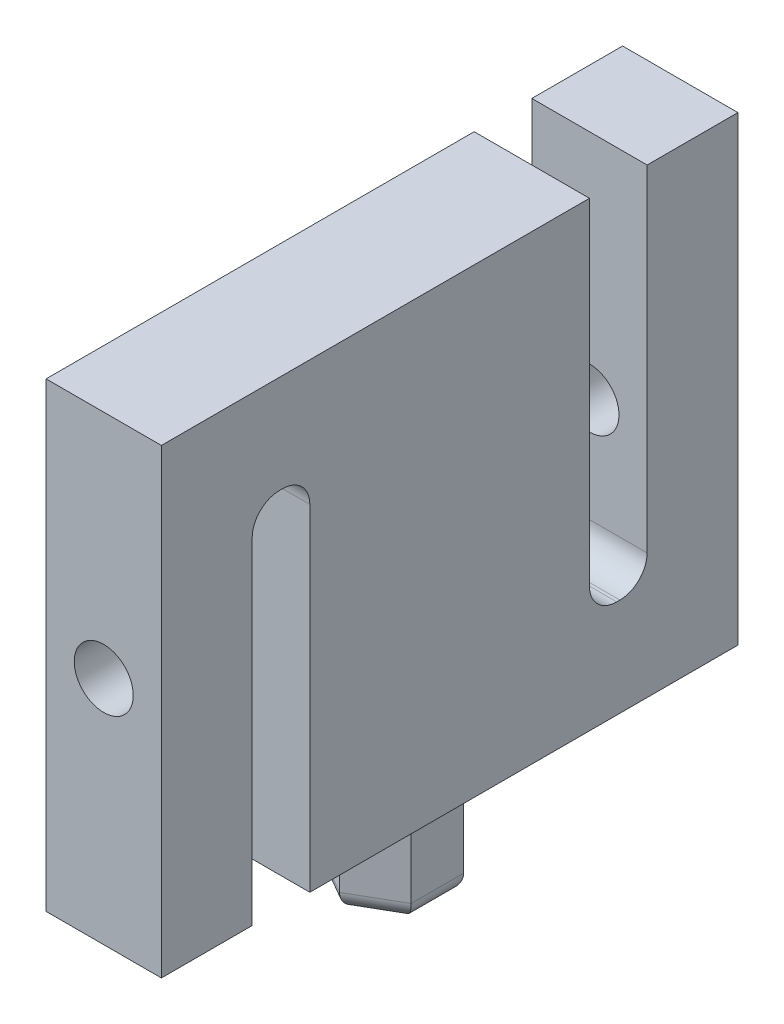
SolidWorks part; units mm, degrees
ref_plane "Front Plane" through (0, 0, 0) normal (0, 0, 1) x (1, 0, 0)
ref_plane "Top Plane" through (0, 0, 0) normal (0, 1, 0) x (1, 0, 0)
ref_plane "Right Plane" through (0, 0, 0) normal (1, 0, 0) x (0, 0, -1)
sketch "Sketch1" plane through (0, 0, 0) normal (1, 0, 0) x (0, 0, -1)
  line L0 (-107.95, 279.4) -> (-44.45, 279.4) construction
  line L12 (-54.45, 304.8) -> (-54.45, 264.8)
  line L13 (-54.45, 264.8) -> (-60.8, 264.8)
  line L14 (-60.8, 264.8) -> (-60.8, 304.8)
  line L15 (-60.8, 304.8) -> (-107.95, 304.8)
  line L16 (-107.95, 304.8) -> (-107.95, 254)
  line L17 (-107.95, 254) -> (-97.95, 254)
  line L18 (-97.95, 254) -> (-97.95, 294)
  line L19 (-97.95, 294) -> (-91.6, 294)
  line L20 (-91.6, 294) -> (-91.6, 254)
  line L21 (-91.6, 254) -> (-44.45, 254)
  line L22 (-44.45, 254) -> (-44.45, 304.8)
  line L23 (-44.45, 304.8) -> (-54.45, 304.8)
  line L24 (-54.45, 304.8) -> (-54.45, 264.8)
  line L25 (-54.45, 264.8) -> (-60.8, 264.8)
  line L26 (-60.8, 264.8) -> (-60.8, 304.8)
  line L27 (-60.8, 304.8) -> (-107.95, 304.8)
  line L28 (-107.95, 304.8) -> (-107.95, 254)
  line L29 (-107.95, 254) -> (-97.95, 254)
  line L30 (-97.95, 254) -> (-97.95, 294)
  line L31 (-97.95, 294) -> (-91.6, 294)
  line L32 (-91.6, 294) -> (-91.6, 254)
  line L33 (-91.6, 254) -> (-44.45, 254)
  line L34 (-44.45, 254) -> (-44.45, 304.8)
  line L35 (-44.45, 304.8) -> (-54.45, 304.8)
  dimension "D1" = 0
extrude "Boss-Extrude1" add sketch "Sketch1" along normal mid plane 12.7
fillet "Fillet1" radius 3 4 edges at (0, 264.8, 60.8) (0, 264.8, 54.45) (0, 294, 91.6) (0, 294, 97.95)
ref_plane "Plane1" through (0, 0, 76.2) normal (0, 0, -1) x (-1, 0, 0)
sketch "Sketch2" plane through (0, 0, 44.45) normal (0, 0, -1) x (-1, 0, 0)
  line L0 (0, 254) -> (0, 304.8) construction
  line L1 (-6.35, 254) -> (6.35, 254) construction
  line L2 (-6.35, 304.8) -> (6.35, 304.8) construction
  circle A0 centre (0, 279.4) radius 3.25
  dimension "D1" = 6.5
extrude "Cut-Extrude1" cut sketch "Sketch2" against normal up to next
cosmetic thread "Cosmetic Thread1" parameters "D2"=8
mirror "Mirror2" about plane through (0, 0, 76.2) normal (0, 0, -1) of "Cut-Extrude1"
cosmetic thread "Cosmetic Thread2" parameters "D2"=8
sketch "Sketch8" plane through (0, 254, 0) normal (0, -1, 0) x (1, 0, 0)
  line L0 (0, 107.95) -> (0, 44.45) construction
  line L1 (6.35, 44.45) -> (-6.35, 44.45) construction
  line L2 (6.35, 107.95) -> (-6.35, 107.95) construction
  line L4 (5, 73.3132) -> (5, 79.0868)
  line L5 (5, 79.0868) -> (0, 81.9735)
  line L6 (0, 81.9735) -> (-5, 79.0868)
  line L7 (-5, 79.0868) -> (-5, 73.3132)
  line L8 (-5, 73.3132) -> (0, 70.4265)
  line L9 (0, 70.4265) -> (5, 73.3132)
  circle A0 centre (0, 76.2) radius 5 construction
  dimension "D1" = 10
extrude "Boss-Extrude2" add sketch "Sketch8" along normal blind 10 separate body
fillet "Fillet2" radius 2 6 edges at (-2.5, 244, 71.8699) (-5, 244, 76.2) (-2.5, 244, 80.5301) (2.5, 244, 80.5301) (5, 244, 76.2) (2.5, 244, 71.8699)
